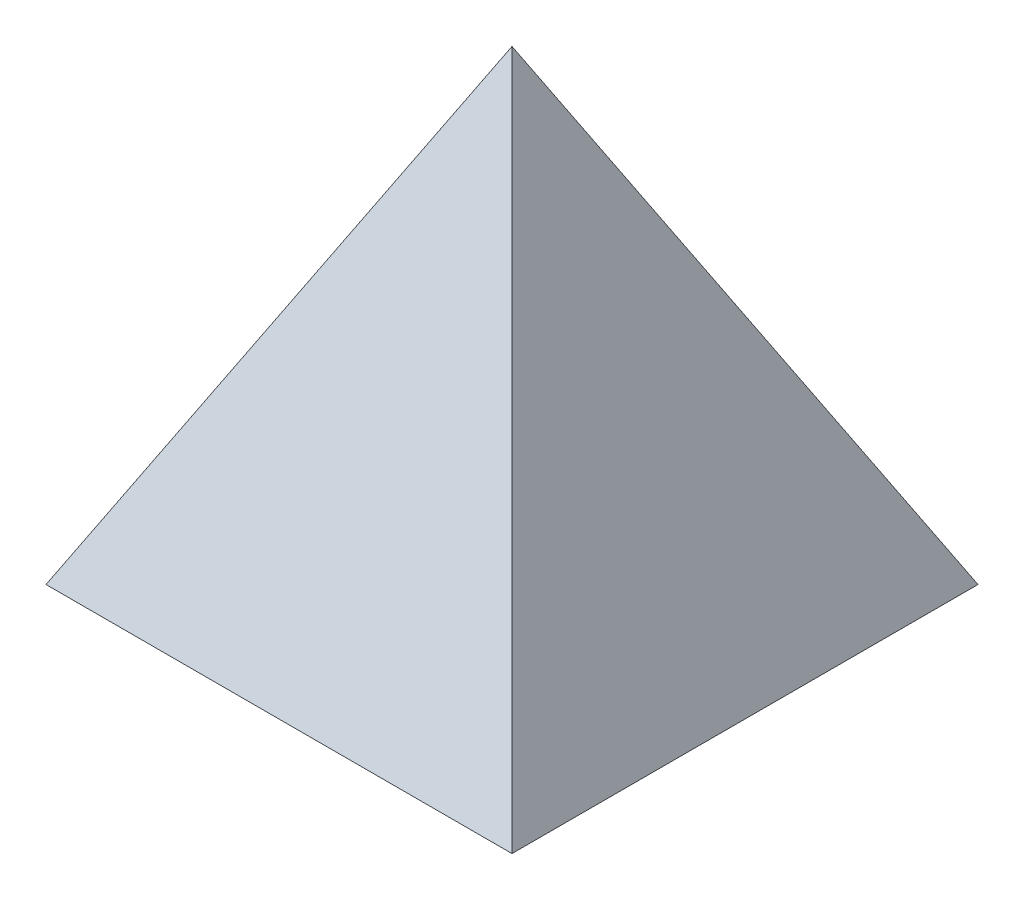
SolidWorks part; units mm, degrees
ref_plane "Front Plane" through (0, 0, 0) normal (0, 0, 1) x (1, 0, 0)
ref_plane "Top Plane" through (0, 0, 0) normal (0, 1, 0) x (1, 0, 0)
ref_plane "Right Plane" through (0, 0, 0) normal (1, 0, 0) x (0, 0, -1)
sketch "Sketch1" plane through (0, 0, 0) normal (0, 1, 0) x (1, 0, 0)
  line L1 (-25, -25) -> (25, -25)
  line L2 (-25, -25) -> (-25, 25)
  line L3 (-25, 25) -> (25, 25)
  line L4 (25, -25) -> (25, 25)
  line L5 (-25, -25) -> (25, 25) construction
  line L6 (-25, 25) -> (25, -25) construction
  point P0 (0, 0)
  dimension "D1" = 50
  dimension "D2" = 50
extrude "Boss-Extrude1" add sketch "Sketch1" along normal blind 50
sketch "Sketch4" plane through (0, 0, 0) normal (1, 0, 0) x (0, 0, -1)
  line L0 (-25, 0) -> (0, 50)
  line L1 (-25, 50) -> (25, 50) construction
  line L2 (0, 50) -> (25, 0)
  line L3 (25, 0) -> (-25, 0)
extrude "Cut-Extrude3" cut sketch "Sketch4" against normal through all flip side to cut
sketch "Sketch5" plane through (0, 0, 0) normal (1, 0, 0) x (0, 0, -1)
  line L0 (-25, 0) -> (0, 50)
  line L1 (-25, 50) -> (25, 50) construction
  line L2 (0, 50) -> (25, 0)
  line L3 (25, 0) -> (-25, 0)
extrude "Cut-Extrude4" cut sketch "Sketch5" along normal through all flip side to cut
sketch "Sketch6" plane through (0, 0, 0) normal (0, 0, 1) x (1, 0, 0)
  line L0 (-25, 0) -> (0, 50)
  line L1 (-25, 50) -> (25, 50) construction
  line L2 (0, 50) -> (25, 0)
  line L3 (25, 0) -> (-25, 0)
extrude "Cut-Extrude5" cut sketch "Sketch6" against normal through all flip side to cut
sketch "Sketch7" plane through (0, 0, 0) normal (0, 0, 1) x (1, 0, 0)
  line L0 (-25, 0) -> (0, 50)
  line L1 (0, 50) -> (25, 0)
  line L2 (25, 0) -> (-25, 0)
extrude "Cut-Extrude6" cut sketch "Sketch7" along normal through all flip side to cut
